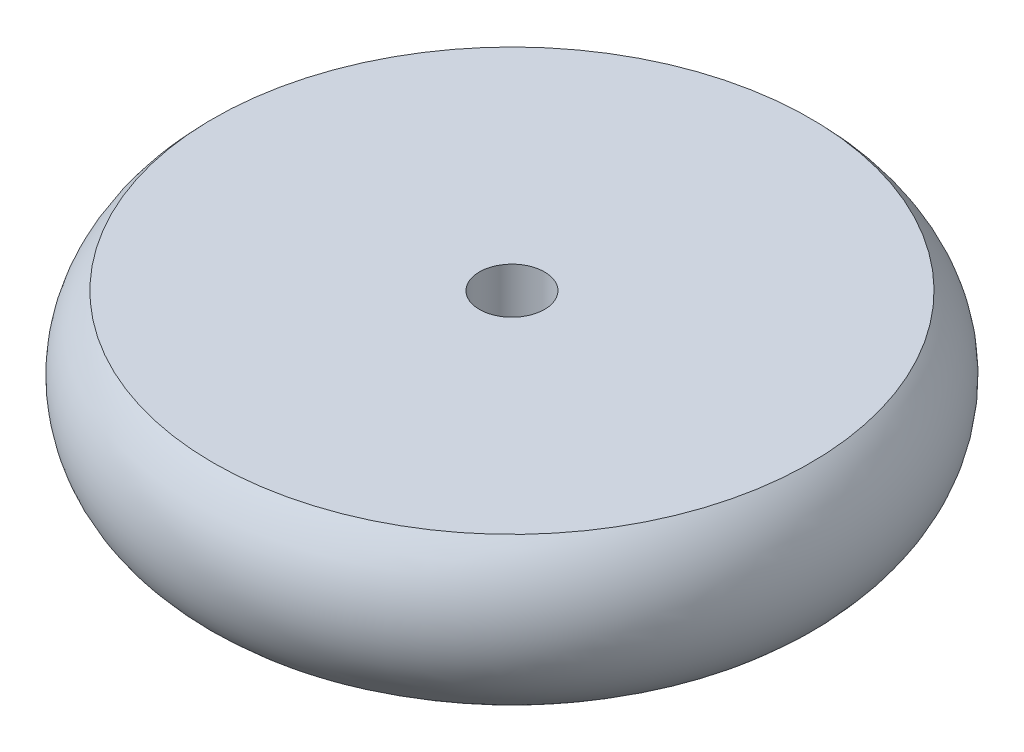
SolidWorks part; units mm, degrees
ref_plane "Plan de face" through (0, 0, 0) normal (0, 0, 1) x (1, 0, 0)
ref_plane "Plan de dessus" through (0, 0, 0) normal (0, 1, 0) x (1, 0, 0)
ref_plane "Plan de droite" through (0, 0, 0) normal (1, 0, 0) x (0, 0, -1)
sketch "Esquisse1" plane through (0, 0, 0) normal (0, 0, 1) x (1, 0, 0)
  line L0 (0, 26.2367) -> (0, -35.7197)
  line L1 (4, 12.5) -> (28, 12.5)
  line L2 (4, 12.5) -> (4, -12.5)
  line L3 (4, -12.5) -> (28, -12.5)
  line L4 (4, 9) -> (36.6747, 9)
  arc A0 (28, -12.5) -> (28, 12.5) centre (28, 0) ccw
  dimension "D1" = 4
  dimension "D2" = 9
  dimension "D3" = 25
  dimension "D4" = 12.5
revolve "Révolution1" add sketch "Esquisse1" angle 360 about L0
